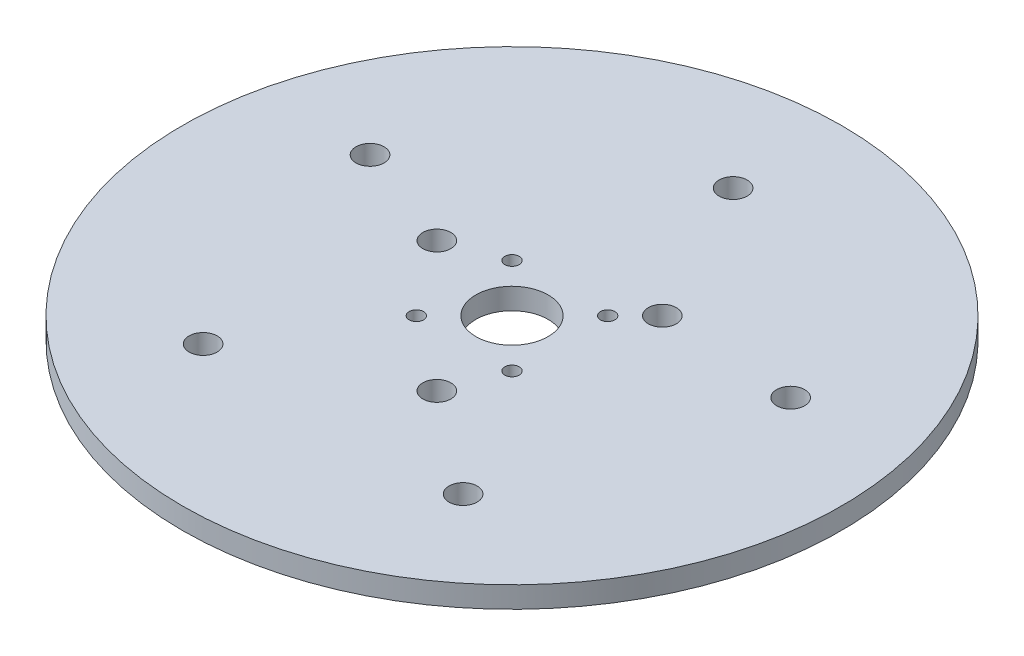
SolidWorks part; units mm, degrees
ref_plane "Front Plane" through (0, 0, 0) normal (0, 0, 1) x (1, 0, 0)
ref_plane "Top Plane" through (0, 0, 0) normal (0, 1, 0) x (1, 0, 0)
ref_plane "Right Plane" through (0, 0, 0) normal (1, 0, 0) x (0, 0, -1)
sketch "Sketch1" plane through (0, 0, 0) normal (0, 1, 0) x (1, 0, 0)
  circle A0 centre (0, 0) radius 77.5
  circle A1 centre (0, 0) radius 8.5
  dimension "D1" = 155
  dimension "D2" = 17
extrude "Body" add sketch "Sketch1" along normal blind 5
hole_wizard "M6 Clearance Hole1" positions "Sketch2" profile "Sketch3" hole size "M6" standard "ANSI Metric" end condition through all
sketch "Sketch2" plane through (0, 5, 0) normal (0, 1, 0) x (1, 0, 0)
  point P0 (0, 52)
  point P10 (49.4549, 16.0689)
  point P11 (30.5648, -42.0689)
  point P12 (-30.5648, -42.0689)
  point P13 (-49.4549, 16.0689)
  point P15 (0, 0)
  point P19 (0, 52)
  dimension "D1" = 52
  dimension "D3" = 5
sketch "Sketch3" plane through (0, 5, -52) normal (1, 0, 0) x (0, 0, 1)
  line L0 (0, 0) -> (0, 5)
  line L1 (0, 5) -> (3.3, 5)
  line L2 (3.3, 5) -> (3.3, 0)
  line L5 (3.3, 0) -> (0, 0)
  line L11 (0, -6.35) -> (0, 107.95) construction
  dimension "Thru Hole Dia." = 6.6
  dimension "Thru Hole Depth" = 5
hole_wizard "M3 Clearance Hole1" positions "Sketch4" profile "Sketch5" hole size "M3" standard "ANSI Metric" end condition through all
sketch "Sketch4" plane through (0, 5, 0) normal (0, 1, 0) x (1, 0, 0)
  line L1 (11.25, -11.25) -> (-11.25, -11.25) construction
  line L2 (11.25, -11.25) -> (11.25, 11.25) construction
  line L3 (11.25, 11.25) -> (-11.25, 11.25) construction
  line L4 (-11.25, -11.25) -> (-11.25, 11.25) construction
  line L5 (11.25, -11.25) -> (-11.25, 11.25) construction
  line L6 (11.25, 11.25) -> (-11.25, -11.25) construction
  point P1 (0, 0)
  point P2 (-11.25, 11.25)
  point P21 (11.25, -11.25)
  point P22 (11.25, 11.25)
  point P23 (-11.25, -11.25)
  dimension "D1" = 22.5
sketch "Sketch5" plane through (0, 5, 0) normal (1, 0, 0) x (0, 0, 1)
  line L0 (0, 0) -> (0, 5)
  line L1 (0, 5) -> (1.7, 5)
  line L2 (1.7, 5) -> (1.7, 0)
  line L5 (1.7, 0) -> (0, 0)
  line L11 (0, -6.35) -> (0, 107.95) construction
  dimension "Thru Hole Dia." = 3.4
  dimension "Thru Hole Depth" = 5
hole_wizard "M6 Clearance Hole2" positions "Sketch7" profile "Sketch8" hole size "M6" standard "ANSI Metric" end condition through all
sketch "Sketch7" plane through (0, 5, 0) normal (0, 1, 0) x (1, 0, 0)
  line L0 (0, -1000) -> (0, 49000) construction
  line L1 (-707.1068, -707.1068) -> (34648.2323, 34648.2323) construction
  circle A0 centre (0, 0) radius 25 construction
  circle A1 centre (0, 0) radius 25 construction
  circle A2 centre (0, 0) radius 25 construction
  point P0 (17.6777, 17.6777)
  point P25 (6.4705, -24.1481)
  point P27 (-24.1481, 6.4705)
  point P29 (0, 0)
  dimension "D1" = 50
  dimension "D2" = 45
  dimension "D3" = 3
sketch "Sketch8" plane through (17.6777, 5, -17.6777) normal (1, 0, 0) x (0, 0, 1)
  line L0 (0, 0) -> (0, 5)
  line L1 (0, 5) -> (3.3, 5)
  line L2 (3.3, 5) -> (3.3, 0)
  line L5 (3.3, 0) -> (0, 0)
  line L11 (0, -6.35) -> (0, 107.95) construction
  dimension "Thru Hole Dia." = 6.6
  dimension "Thru Hole Depth" = 5
